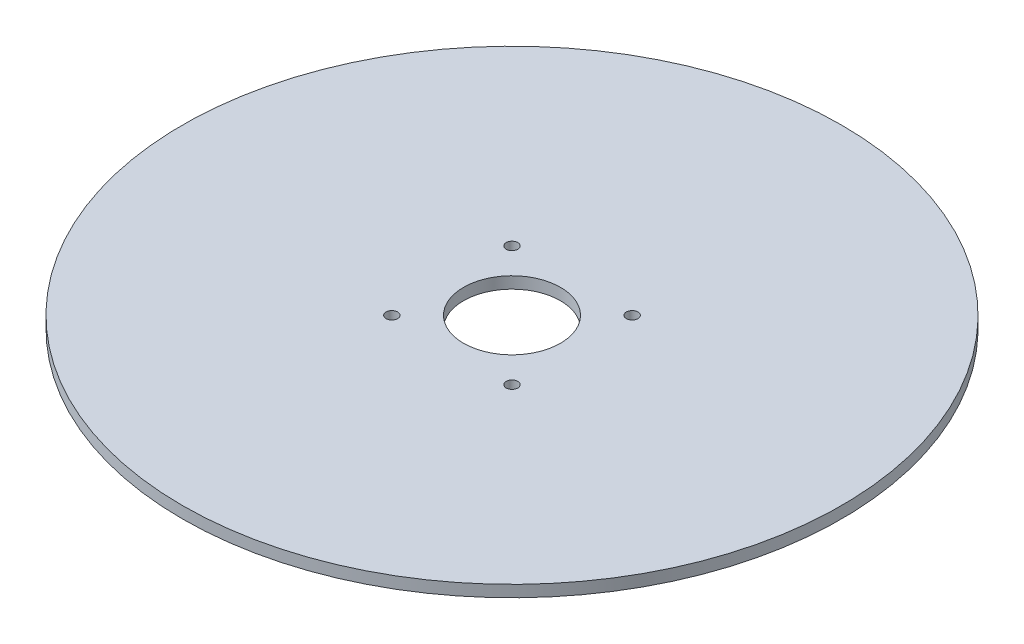
SolidWorks part; units mm, degrees
ref_plane "Front Plane" through (0, 0, 0) normal (0, 0, 1) x (1, 0, 0)
ref_plane "Top Plane" through (0, 0, 0) normal (0, 1, 0) x (1, 0, 0)
ref_plane "Right Plane" through (0, 0, 0) normal (1, 0, 0) x (0, 0, -1)
sketch "Sketch1" plane through (0, 0, 0) normal (0, 1, 0) x (1, 0, 0)
  circle A0 centre (0, 0) radius 85
  circle A1 centre (0, 0) radius 12.5
  dimension "D1" = 170
  dimension "D2" = 25
extrude "Boss-Extrude1" add sketch "Sketch1" along normal blind 3
sketch "Sketch2" plane through (0, 3, 0) normal (0, 1, 0) x (1, 0, 0)
  line L1 (-15.5, -15.5) -> (15.5, -15.5)
  line L2 (-15.5, -15.5) -> (-15.5, 15.5)
  line L3 (-15.5, 15.5) -> (15.5, 15.5)
  line L4 (15.5, -15.5) -> (15.5, 15.5)
  line L5 (-15.5, -15.5) -> (15.5, 15.5) construction
  line L6 (-15.5, 15.5) -> (15.5, -15.5) construction
  circle A0 centre (15.5, 15.5) radius 1.5
  circle A1 centre (-15.5, 15.5) radius 1.5
  circle A2 centre (-15.5, -15.5) radius 1.5
  circle A3 centre (15.5, -15.5) radius 1.5
  point P0 (0, 0)
  dimension "D1" = 3
  dimension "D4" = 3
  dimension "D5" = 3
  dimension "D6" = 3
  dimension "D2" = 31
  dimension "D3" = 31
extrude "Cut-Extrude1" cut sketch "Sketch2" against normal blind 10 contours L3 A1 L2 | L2 A1 L3 | L4 A0 L3 | L3 A0 L4 | L4 A3 L1 | L1 A3 L4 | L1 A2 L2 | L2 A2 L1
